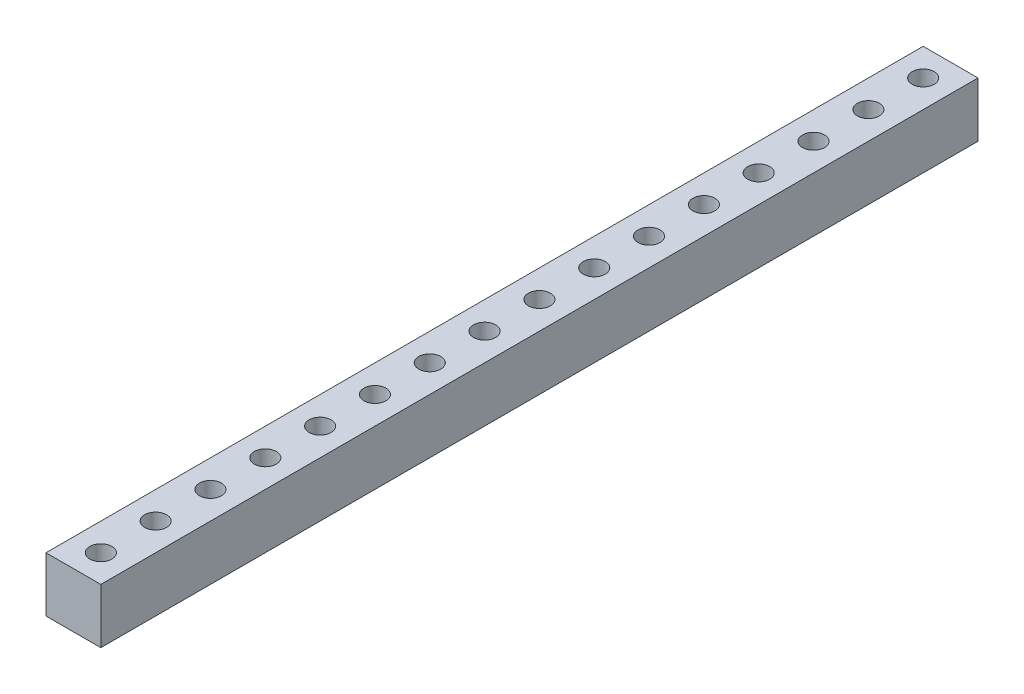
SolidWorks part; units mm, degrees
ref_plane "Front Plane" through (0, 0, 0) normal (0, 0, 1) x (1, 0, 0)
ref_plane "Top Plane" through (0, 0, 0) normal (0, 1, 0) x (1, 0, 0)
ref_plane "Right Plane" through (0, 0, 0) normal (1, 0, 0) x (0, 0, -1)
sketch "Sketch1" plane through (0, 0, 0) normal (1, 0, 0) x (0, 0, -1)
  line L1 (-20.32, -1.27) -> (20.32, -1.27)
  line L2 (-20.32, -1.27) -> (-20.32, 1.27)
  line L3 (-20.32, 1.27) -> (20.32, 1.27)
  line L4 (20.32, -1.27) -> (20.32, 1.27)
  line L5 (-20.32, -1.27) -> (20.32, 1.27) construction
  line L6 (-20.32, 1.27) -> (20.32, -1.27) construction
  point P0 (0, 0)
  dimension "D1" = 40.64
  dimension "D2" = 2.54
extrude "Boss-Extrude1" add sketch "Sketch1" along normal blind 2.54
sketch "Sketch2" plane through (0, 1.27, 0) normal (0, 1, 0) x (1, 0, 0)
  line L0 (1.27, 20.32) -> (1.27, -20.32) construction
  line L1 (2.54, 20.32) -> (0, 20.32) construction
  line L2 (2.54, -20.32) -> (0, -20.32) construction
  line L3 (1.27, -20.32) -> (1.27, -19.05) construction
hole_wizard "Ø1.0mm Dowel Hole1" positions "3DSketch1" profile "Sketch3" hole size "Ø1.0" standard "ANSI Metric" end condition through all
sketch3d "3DSketch1"
  point P0 (1.27, 1.27, 19.05)
sketch "Sketch3" plane through (1.27, 1.27, 19.05) normal (1, 0, 0) x (0, 0, 1)
  line L0 (0, 0) -> (0, 2.54)
  line L1 (0, 2.54) -> (0.51, 2.54)
  line L2 (0.51, 2.54) -> (0.51, 0)
  line L5 (0.51, 0) -> (0, 0)
  line L11 (0, -6.35) -> (0, 107.95) construction
  dimension "Thru Hole Dia." = 1.02
  dimension "Thru Hole Depth" = 2.54
pattern_linear "LPattern1" count 16 spacing 2.54 along (0, 0, -1) of "Ø1.0mm Dowel Hole1"
